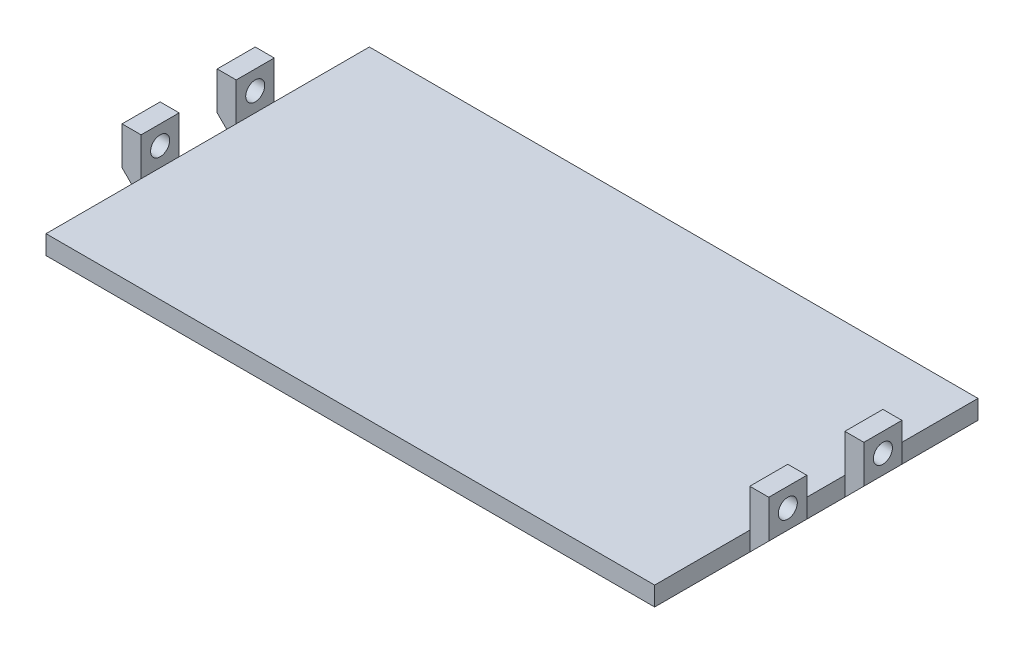
SolidWorks part; units mm, degrees
ref_plane "Front Plane" through (0, 0, 0) normal (0, 0, 1) x (1, 0, 0)
ref_plane "Top Plane" through (0, 0, 0) normal (0, 1, 0) x (1, 0, 0)
ref_plane "Right Plane" through (0, 0, 0) normal (1, 0, 0) x (0, 0, -1)
sketch "Sketch1" plane through (0, 0, 0) normal (0, 1, 0) x (1, 0, 0)
  line L1 (-85, 42.5) -> (85, 42.5)
  line L2 (-85, 42.5) -> (-85, -42.5)
  line L3 (-85, -42.5) -> (85, -42.5)
  line L4 (85, 42.5) -> (85, -42.5)
  line L5 (-85, 42.5) -> (85, -42.5) construction
  line L6 (-85, -42.5) -> (85, 42.5) construction
  point P0 (0, 0)
  dimension "D1" = 170
  dimension "D2" = 85
extrude "Boss-Extrude1" add sketch "Sketch1" along normal blind 5
sketch "Sketch2" plane through (0, 5, 0) normal (0, 1, 0) x (1, 0, 0)
  line L0 (-85, 42.5) -> (-85, -42.5) construction
  line L1 (-85, 17.5) -> (-80, 17.5)
  line L2 (-85, 17.5) -> (-85, 7.5)
  line L3 (-85, 7.5) -> (-80, 7.5)
  line L4 (-80, 17.5) -> (-80, 7.5)
  line L6 (-85, -7.5) -> (-80, -7.5)
  line L7 (-85, -7.5) -> (-85, -17.5)
  line L8 (-85, -17.5) -> (-80, -17.5)
  line L9 (-80, -7.5) -> (-80, -17.5)
  line L10 (-85, 12.5) -> (-80, 12.5) construction
  line L11 (-85, -12.5) -> (-80, -12.5) construction
  line L14 (85, 42.5) -> (-85, 42.5) construction
  line L16 (0, 0) -> (0, -27.3364) construction
  line L17 (85, -12.5) -> (80, -12.5) construction
  line L18 (85, 12.5) -> (80, 12.5) construction
  line L19 (80, -7.5) -> (80, -17.5)
  line L20 (85, -17.5) -> (80, -17.5)
  line L21 (85, -7.5) -> (85, -17.5)
  line L22 (85, -7.5) -> (80, -7.5)
  line L23 (80, 17.5) -> (80, 7.5)
  line L24 (85, 7.5) -> (80, 7.5)
  line L25 (85, 17.5) -> (85, 7.5)
  line L26 (85, 17.5) -> (80, 17.5)
  dimension "D1" = 30
  dimension "D2" = 10
  dimension "D3" = 10
  dimension "D4" = 25
  dimension "D5" = 5
  dimension "D6" = 5
extrude "Boss-Extrude2" add sketch "Sketch2" along normal blind 10
sketch "Sketch3" plane through (-85, 0, 0) normal (-1, 0, 0) x (0, 0, 1)
  line L0 (7.5, 15) -> (17.5, 15) construction
  line L1 (-17.5, 15) -> (-7.5, 15) construction
  line L2 (-17.5, 15) -> (-17.5, 5) construction
  line L3 (7.5, 15) -> (7.5, 5) construction
  circle A0 centre (-12.5, 10) radius 2.5
  circle A1 centre (12.5, 10) radius 2.5
  dimension "D1" = 5
  dimension "D2" = 5
  dimension "D3" = 5
  dimension "D4" = 5
  dimension "D5" = 5
  dimension "D6" = 5
extrude "Cut-Extrude1" cut sketch "Sketch3" against normal through all
sketch "Sketch4" plane through (0, 5, 0) normal (0, 1, 0) x (1, 0, 0)
  line L0 (-85, -42.5) -> (85, -42.5) construction
  line L1 (-85, 42.5) -> (-80, 42.5)
  line L2 (-85, 42.5) -> (-85, 17.5)
  line L3 (-85, 17.5) -> (-80, 17.5)
  line L4 (-80, 42.5) -> (-80, 17.5)
  line L5 (-85, -17.5) -> (-80, -17.5)
  line L6 (-85, -17.5) -> (-85, -42.5)
  line L7 (-85, -42.5) -> (-80, -42.5)
  line L8 (-80, -17.5) -> (-80, -42.5)
  line L10 (-85, 7.5) -> (-80, 7.5)
  line L11 (-85, 7.5) -> (-85, -7.5)
  line L12 (-85, -7.5) -> (-80, -7.5)
  line L13 (-80, 7.5) -> (-80, -7.5)
  line L14 (80, 7.5) -> (85, 7.5)
  line L15 (80, 7.5) -> (80, -7.5)
  line L16 (80, -7.5) -> (85, -7.5)
  line L17 (85, 7.5) -> (85, -7.5)
  line L18 (85, 42.5) -> (80, 42.5)
  line L19 (85, 42.5) -> (85, 17.5)
  line L20 (85, 17.5) -> (80, 17.5)
  line L21 (80, 42.5) -> (80, 17.5)
  line L22 (80, -17.5) -> (85, -17.5)
  line L23 (80, -17.5) -> (80, -42.5)
  line L24 (80, -42.5) -> (85, -42.5)
  line L25 (85, -17.5) -> (85, -42.5)
extrude "Cut-Extrude2" cut sketch "Sketch4" against normal through all
chamfer "Chamfer1" distance 5 angle 45 4 edges at (85, 0, 12.5) (85, 0, -12.5) (-85, 0, 12.5) (-85, 0, -12.5)
